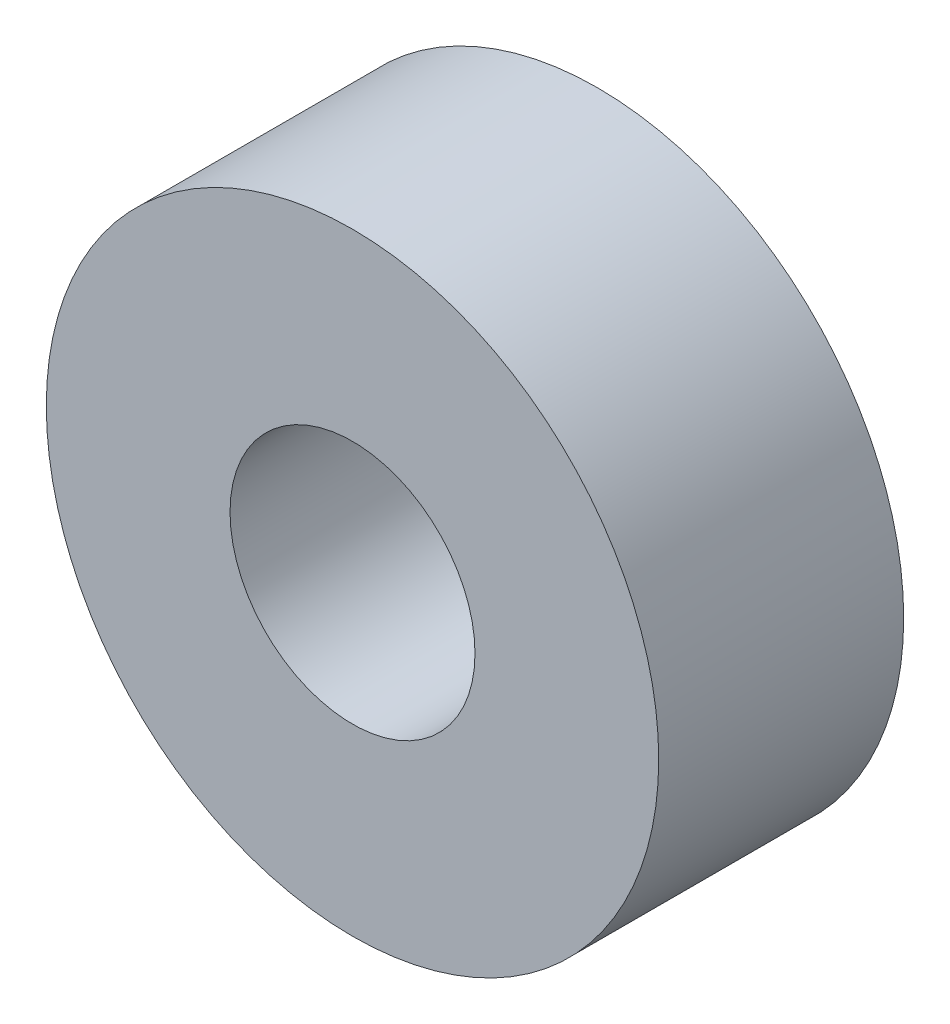
SolidWorks part; units mm, degrees
ref_plane "前视基准面" through (0, 0, 0) normal (0, 0, 1) x (1, 0, 0)
ref_plane "上视基准面" through (0, 0, 0) normal (0, 1, 0) x (1, 0, 0)
ref_plane "右视基准面" through (0, 0, 0) normal (1, 0, 0) x (0, 0, -1)
sketch "草图1" plane through (0, 0, 0) normal (0, 0, 1) x (1, 0, 0)
  circle A0 centre (0, 0) radius 2
  circle A1 centre (0, 0) radius 5
extrude "凸台-拉伸1" add sketch "草图1" along normal blind 4
